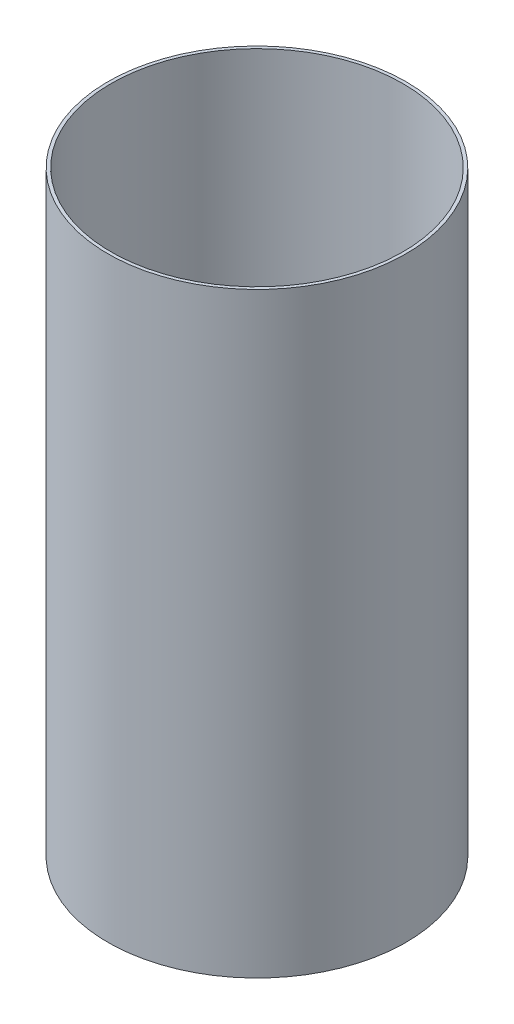
SolidWorks part; units mm, degrees
material "A-Glass Fiber"
ref_plane "Front Plane" through (0, 0, 0) normal (0, 0, 1) x (1, 0, 0)
ref_plane "Top Plane" through (0, 0, 0) normal (0, 1, 0) x (1, 0, 0)
ref_plane "Right Plane" through (0, 0, 0) normal (1, 0, 0) x (0, 0, -1)
sketch "Sketch1" plane through (0, 0, 0) normal (0, 1, 0) x (1, 0, 0)
  circle A0 centre (0, 0) radius 78.35
  circle A1 centre (0, 0) radius 76.67
  dimension "D1" = 156.7
  dimension "D2" = 1.68
extrude "Boss-Extrude1" add sketch "Sketch1" along normal blind 313.4
